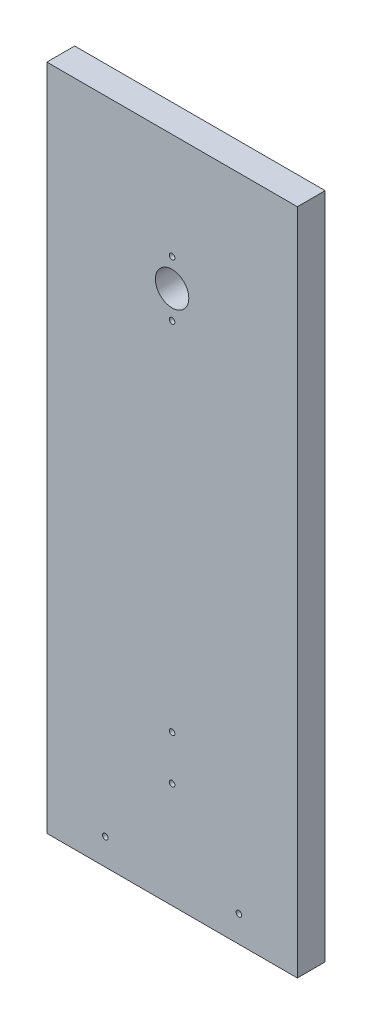
SolidWorks part; units mm, degrees
ref_plane "Plan de face" through (0, 0, 0) normal (0, 0, 1) x (1, 0, 0)
ref_plane "Plan de dessus" through (0, 0, 0) normal (0, 1, 0) x (1, 0, 0)
ref_plane "Plan de droite" through (0, 0, 0) normal (1, 0, 0) x (0, 0, -1)
sketch "Esquisse1" plane through (0, 0, 0) normal (0, 0, 1) x (1, 0, 0)
  line L1 (0, 0) -> (90, 0)
  line L2 (0, 0) -> (0, 240)
  line L3 (0, 240) -> (90, 240)
  line L4 (90, 0) -> (90, 240)
  dimension "D1" = 90
  dimension "D2" = 240
extrude "Boss.-Extru.1" add sketch "Esquisse1" along normal blind 10
sketch "Esquisse2" plane through (0, 0, 10) normal (0, 0, 1) x (1, 0, 0)
  line L0 (45, 0) -> (45, 54) construction
  line L1 (0, 0) -> (90, 0) construction
  line L2 (45, 9.5) -> (21, 9.5) construction
  line L3 (45, 0) -> (45, 192) construction
  line L4 (45, 192) -> (27.8128, 192) construction
  circle A0 centre (45, 54) radius 1
  circle A1 centre (45, 38) radius 1
  circle A2 centre (21, 9.5) radius 1
  circle A3 centre (69, 9.5) radius 1
  circle A4 centre (45, 192) radius 6
  circle A5 centre (45, 182) radius 1
  circle A6 centre (45, 202) radius 1
  dimension "D1" = 2
  dimension "D2" = 16
  dimension "D4" = 2
  dimension "D5" = 48
  dimension "D7" = 12
  dimension "D9" = 2
  dimension "D10" = 10
  dimension "D3" = 38
  dimension "D6" = 9.5
  dimension "D8" = 192
extrude "Enlèv. mat.-Extru.1" cut sketch "Esquisse2" against normal through all both and the other way through all
